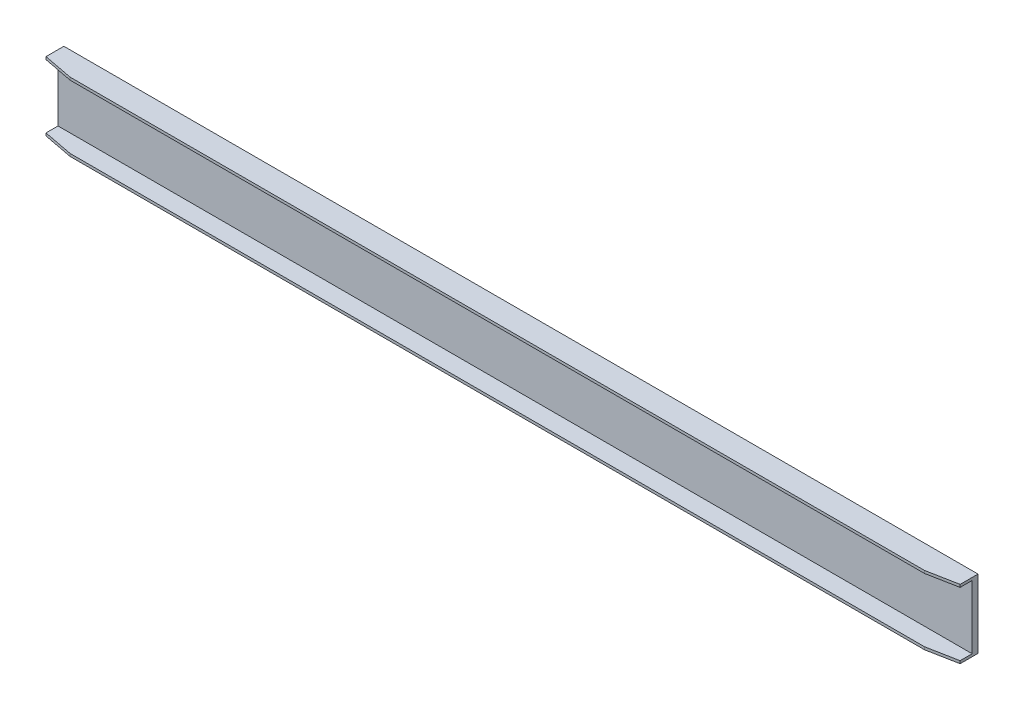
SolidWorks part; units mm, degrees
ref_plane "前视" through (0, 0, 0) normal (0, 0, 1) x (1, 0, 0)
ref_plane "上视" through (0, 0, 0) normal (0, 1, 0) x (1, 0, 0)
ref_plane "右视" through (0, 0, 0) normal (1, 0, 0) x (0, 0, -1)
sketch "草图1" plane through (0, 0, 0) normal (0, 0, 1) x (1, 0, 0)
  line L0 (0, 280.187) -> (0, -298.191) construction
  line L1 (-2057.2074, 0) -> (2116.7847, 0) construction
  line L2 (2116.7847, 80) -> (-2430.1435, 80) construction
  line L3 (-1995, 150) -> (1995, 150)
  line L5 (-1995, -150) -> (1995, -150)
  line L6 (1995, 150) -> (1995, -150)
  line L7 (-2430.1435, -80) -> (2116.7847, -80) construction
  line L8 (1940, 266.4652) -> (1940, -249.2739) construction
  line L9 (1860, -249.2739) -> (1860, 266.4652) construction
  line L10 (1060, 266.4652) -> (1060, -361.7988) construction
  line L11 (1780, 266.4652) -> (1780, -249.2739) construction
  line L12 (1780, -249.2739) -> (1700, -249.2739) construction
  line L13 (1700, -249.2739) -> (1700, 266.4652) construction
  line L14 (1540, 266.4652) -> (1540, -361.7988) construction
  line L15 (1380, 266.4652) -> (1380, -361.7988) construction
  line L16 (1220, -361.7988) -> (1220, 266.4652) construction
  line L17 (980, -361.7988) -> (980, 266.4652) construction
  line L18 (740, -361.7988) -> (740, 464.33) construction
  line L19 (820, 266.4652) -> (820, -361.7988) construction
  line L20 (580, -361.7988) -> (580, 266.4652) construction
  line L21 (420, -361.7988) -> (420, 266.4652) construction
  line L22 (300, -298.191) -> (300, 266.4652) construction
  line L23 (60, 280.187) -> (60, -298.191) construction
  line L24 (140, 280.187) -> (140, -298.191) construction
  line L25 (220, -298.191) -> (220, 280.187) construction
  line L26 (-1995, 150) -> (-1995, -150)
  circle A0 centre (1940, 80) radius 13
  circle A1 centre (1860, 80) radius 13
  circle A2 centre (1780, 80) radius 13
  circle A3 centre (1700, 80) radius 13
  circle A4 centre (1540, 80) radius 11.5
  circle A5 centre (1380, 80) radius 11.5
  circle A6 centre (1220, 80) radius 11.5
  circle A7 centre (1060, 80) radius 11.5
  circle A8 centre (980, 80) radius 11.5
  circle A9 centre (820, 80) radius 11.5
  circle A10 centre (740, 80) radius 11.5
  circle A11 centre (580, 80) radius 11.5
  circle A12 centre (980, 0) radius 11.5
  circle A13 centre (1060, 0) radius 11.5
  circle A14 centre (820, 0) radius 11.5
  circle A15 centre (740, 0) radius 11.5
  circle A16 centre (580, 0) radius 11.5
  circle A17 centre (1220, 0) radius 11.5
  circle A18 centre (1380, 0) radius 11.5
  circle A19 centre (1540, 0) radius 11.5
  circle A20 centre (1700, 0) radius 13
  circle A21 centre (1780, 0) radius 13
  circle A22 centre (1860, 0) radius 13
  circle A23 centre (1940, 0) radius 13
  circle A24 centre (420, 80) radius 11.5
  circle A25 centre (420, 0) radius 11.5
  circle A26 centre (300, 0) radius 11.5
  circle A27 centre (300, 80) radius 11.5
  circle A28 centre (220, 80) radius 11.5
  circle A29 centre (220, 0) radius 11.5
  circle A30 centre (140, 0) radius 13
  circle A31 centre (140, 80) radius 13
  circle A32 centre (60, 80) radius 13
  circle A33 centre (60, 0) radius 13
  circle A34 centre (1700, -80) radius 13
  circle A35 centre (1780, -80) radius 13
  circle A36 centre (1860, -80) radius 13
  circle A37 centre (1940, -80) radius 13
  circle A38 centre (580, -80) radius 11.5
  circle A39 centre (740, -80) radius 11.5
  circle A40 centre (820, -80) radius 11.5
  circle A41 centre (980, -80) radius 11.5
  circle A42 centre (1060, -80) radius 11.5
  circle A43 centre (1220, -80) radius 11.5
  circle A44 centre (1380, -80) radius 11.5
  circle A45 centre (1540, -80) radius 11.5
  circle A46 centre (220, -80) radius 11.5
  circle A47 centre (300, -80) radius 11.5
  circle A48 centre (420, -80) radius 11.5
  circle A49 centre (580, -80) radius 11.5
  circle A50 centre (60, -80) radius 13
  circle A51 centre (140, -80) radius 13
  circle A52 centre (-140, -80) radius 13
  circle A53 centre (-60, -80) radius 13
  circle A54 centre (-580, -80) radius 11.5
  circle A55 centre (-420, -80) radius 11.5
  circle A56 centre (-300, -80) radius 11.5
  circle A57 centre (-220, -80) radius 11.5
  circle A58 centre (-1540, -80) radius 11.5
  circle A59 centre (-1380, -80) radius 11.5
  circle A60 centre (-1220, -80) radius 11.5
  circle A61 centre (-1060, -80) radius 11.5
  circle A62 centre (-980, -80) radius 11.5
  circle A63 centre (-820, -80) radius 11.5
  circle A64 centre (-740, -80) radius 11.5
  circle A65 centre (-580, -80) radius 11.5
  circle A66 centre (-1940, -80) radius 13
  circle A67 centre (-1860, -80) radius 13
  circle A68 centre (-1780, -80) radius 13
  circle A69 centre (-1700, -80) radius 13
  circle A70 centre (-60, 0) radius 13
  circle A71 centre (-60, 80) radius 13
  circle A72 centre (-140, 80) radius 13
  circle A73 centre (-140, 0) radius 13
  circle A74 centre (-220, 0) radius 11.5
  circle A75 centre (-220, 80) radius 11.5
  circle A76 centre (-300, 80) radius 11.5
  circle A77 centre (-300, 0) radius 11.5
  circle A78 centre (-420, 0) radius 11.5
  circle A79 centre (-420, 80) radius 11.5
  circle A80 centre (-1940, 0) radius 13
  circle A81 centre (-1860, 0) radius 13
  circle A82 centre (-1780, 0) radius 13
  circle A83 centre (-1700, 0) radius 13
  circle A84 centre (-1540, 0) radius 11.5
  circle A85 centre (-1380, 0) radius 11.5
  circle A86 centre (-1220, 0) radius 11.5
  circle A87 centre (-580, 0) radius 11.5
  circle A88 centre (-740, 0) radius 11.5
  circle A89 centre (-820, 0) radius 11.5
  circle A90 centre (-1060, 0) radius 11.5
  circle A91 centre (-980, 0) radius 11.5
  circle A92 centre (-580, 80) radius 11.5
  circle A93 centre (-740, 80) radius 11.5
  circle A94 centre (-820, 80) radius 11.5
  circle A95 centre (-980, 80) radius 11.5
  circle A96 centre (-1060, 80) radius 11.5
  circle A97 centre (-1220, 80) radius 11.5
  circle A98 centre (-1380, 80) radius 11.5
  circle A99 centre (-1540, 80) radius 11.5
  circle A100 centre (-1700, 80) radius 13
  circle A101 centre (-1780, 80) radius 13
  circle A102 centre (-1860, 80) radius 13
  circle A103 centre (-1940, 80) radius 13
  dimension "D22" = 23
  dimension "D23" = 26
  dimension "D24" = 26
  dimension "D1" = 3990
  dimension "D2" = 300
  dimension "D3" = 70
  dimension "D4" = 80
  dimension "D5" = 55
  dimension "D6" = 80
  dimension "D7" = 80
  dimension "D8" = 80
  dimension "D9" = 455
  dimension "D10" = 160
  dimension "D11" = 160
  dimension "D12" = 160
  dimension "D13" = 80
  dimension "D14" = 160
  dimension "D15" = 80
  dimension "D16" = 160
  dimension "D17" = 160
  dimension "D18" = 120
  dimension "D19" = 60
  dimension "D20" = 80
  dimension "D21" = 80
extrude "基体-拉伸" add sketch "草图1" along normal blind 25.5
sketch "草图2" plane through (0, 0, 25.5) normal (0, 0, 1) x (1, 0, 0)
  line L0 (1995, -150) -> (1995, 150) construction
  line L1 (-1995, 150) -> (1995, 150)
  line L2 (-1995, 150) -> (-1995, 138.5)
  line L3 (-1995, 138.5) -> (1995, 138.5)
  line L4 (1995, 150) -> (1995, 138.5)
  line L5 (0, 0) -> (2507.3409, 0) construction
  line L6 (1995, -150) -> (1995, -138.5)
  line L7 (-1995, -138.5) -> (1995, -138.5)
  line L8 (-1995, -150) -> (-1995, -138.5)
  line L9 (-1995, -150) -> (1995, -150)
  dimension "D1" = 11.5
extrude "凸台-拉伸1" add sketch "草图2" along normal blind 77.5
sketch "草图3" plane through (0, 0, 0) normal (0, 0, -1) x (-1, 0, 0)
  line L0 (0, 0) -> (2381.8358, 0) construction
  line L1 (0, 348.8193) -> (0, -302.4645) construction
  line L2 (1300, 348.8193) -> (1300, -385.903) construction
  line L3 (1995, 150) -> (1995, -150) construction
  line L4 (900, 237.7997) -> (900, -385.903) construction
  line L5 (1265, 115) -> (1335, 115)
  line L6 (1265, 115) -> (1265, -115)
  line L7 (1265, -115) -> (1335, -115)
  line L8 (1335, 115) -> (1335, -115)
  line L9 (865, 115) -> (935, 115)
  line L10 (865, 115) -> (865, -115)
  line L11 (865, -115) -> (935, -115)
  line L12 (935, 115) -> (935, -115)
  line L13 (500, -385.903) -> (500, 237.7997) construction
  line L14 (-1265, 115) -> (-1335, 115)
  line L15 (535, -115) -> (465, -115)
  line L16 (535, -115) -> (535, 115)
  line L17 (535, 115) -> (465, 115)
  line L18 (465, -115) -> (465, 115)
  line L19 (-1335, 115) -> (-1335, -115)
  line L20 (-1265, 115) -> (-1265, -115)
  line L21 (-1265, -115) -> (-1335, -115)
  line L22 (-865, -115) -> (-935, -115)
  line L23 (-935, 115) -> (-935, -115)
  line L24 (-865, 115) -> (-935, 115)
  line L25 (-865, 115) -> (-865, -115)
  line L26 (-535, -115) -> (-535, 115)
  line L27 (-535, -115) -> (-465, -115)
  line L28 (-465, -115) -> (-465, 115)
  line L29 (-535, 115) -> (-465, 115)
  dimension "D1" = 695
  dimension "D2" = 70
  dimension "D3" = 230
  dimension "D4" = 400
  dimension "D5" = 70
  dimension "D6" = 230
  dimension "D7" = 400
  dimension "D8" = 70
  dimension "D9" = 230
extrude "凸台-拉伸2" add sketch "草图3" along normal blind 16
sketch "草图4" plane through (0, 0, 25.5) normal (0, 0, 1) x (1, 0, 0)
  line L0 (0, 0) -> (2249.2348, 0) construction
  line L1 (0, 0) -> (0, 1256.1111) construction
  line L2 (1300, 296.2067) -> (1300, -332.3633) construction
  line L3 (900, -332.3633) -> (900, 296.2067) construction
  line L4 (1995, -138.5) -> (1995, 138.5) construction
  line L5 (500, 260.05) -> (500, -332.3633) construction
  line L6 (1458.5104, 80) -> (376.6321, 80) construction
  circle A0 centre (1300, 80) radius 13
  circle A1 centre (900, 80) radius 13
  circle A2 centre (900, 0) radius 13
  circle A3 centre (1300, 0) radius 13
  circle A4 centre (900, -80) radius 13
  circle A5 centre (1300, -80) radius 13
  circle A6 centre (500, 80) radius 13
  circle A7 centre (500, 0) radius 13
  circle A8 centre (500, -80) radius 13
  circle A9 centre (-500, -80) radius 13
  circle A10 centre (-500, 0) radius 13
  circle A11 centre (-500, 80) radius 13
  circle A12 centre (-1300, -80) radius 13
  circle A13 centre (-900, -80) radius 13
  circle A14 centre (-1300, 0) radius 13
  circle A15 centre (-900, 0) radius 13
  circle A16 centre (-900, 80) radius 13
  circle A17 centre (-1300, 80) radius 13
  dimension "D5" = 26
  dimension "D1" = 695
  dimension "D2" = 400
  dimension "D3" = 400
  dimension "D4" = 80
extrude "切除-拉伸1" cut sketch "草图4" against normal through all
sketch "草图5" plane through (0, 150, 0) normal (0, 1, 0) x (-1, 0, 0)
  line L0 (-1995, 78) -> (-1995, 103)
  line L1 (-1995, 103) -> (-1995, 0) construction
  line L2 (-1995, 103) -> (-1865, 103)
  line L3 (-1995, 103) -> (1995, 103) construction
  line L4 (-1865, 103) -> (-1995, 78)
  line L5 (0, 174.8481) -> (0, -119.4889) construction
  line L6 (1865, 103) -> (1995, 78)
  line L7 (1995, 103) -> (1865, 103)
  line L8 (1995, 78) -> (1995, 103)
  dimension "D1" = 130
  dimension "D2" = 25
extrude "切除-拉伸2" cut sketch "草图5" against normal through all
sketch "草图6" plane through (0, 0, 25.5) normal (0, 0, 1) x (1, 0, 0)
  line L1 (-1995, 138.5) -> (1995, 138.5)
  line L2 (-1995, 138.5) -> (-1995, -138.5)
  line L3 (-1995, -138.5) -> (1995, -138.5)
  line L4 (1995, 138.5) -> (1995, -138.5)
extrude "凸台-拉伸3" add sketch "草图6" against normal blind 25.5
sketch "草图7" plane through (0, 0, 0) normal (0, 0, -1) x (-1, 0, 0)
  line L1 (-1335, 115) -> (-1265, 115)
  line L2 (-1335, 115) -> (-1335, -115)
  line L3 (-1335, -115) -> (-1265, -115)
  line L4 (-1265, 115) -> (-1265, -115)
  line L5 (-935, 115) -> (-865, 115)
  line L6 (-935, 115) -> (-935, -115)
  line L7 (-935, -115) -> (-865, -115)
  line L8 (-865, 115) -> (-865, -115)
  line L9 (-535, 115) -> (-465, 115)
  line L10 (-535, 115) -> (-535, -115)
  line L11 (-535, -115) -> (-465, -115)
  line L12 (-465, 115) -> (-465, -115)
  line L13 (465, 115) -> (535, 115)
  line L14 (465, 115) -> (465, -115)
  line L15 (465, -115) -> (535, -115)
  line L16 (535, 115) -> (535, -115)
  line L17 (865, 115) -> (935, 115)
  line L18 (865, 115) -> (865, -115)
  line L19 (865, -115) -> (935, -115)
  line L20 (935, 115) -> (935, -115)
  line L21 (1265, 115) -> (1335, 115)
  line L22 (1265, 115) -> (1265, -115)
  line L23 (1265, -115) -> (1335, -115)
  line L24 (1335, 115) -> (1335, -115)
extrude "凸台-拉伸4" add sketch "草图7" along normal blind 16
